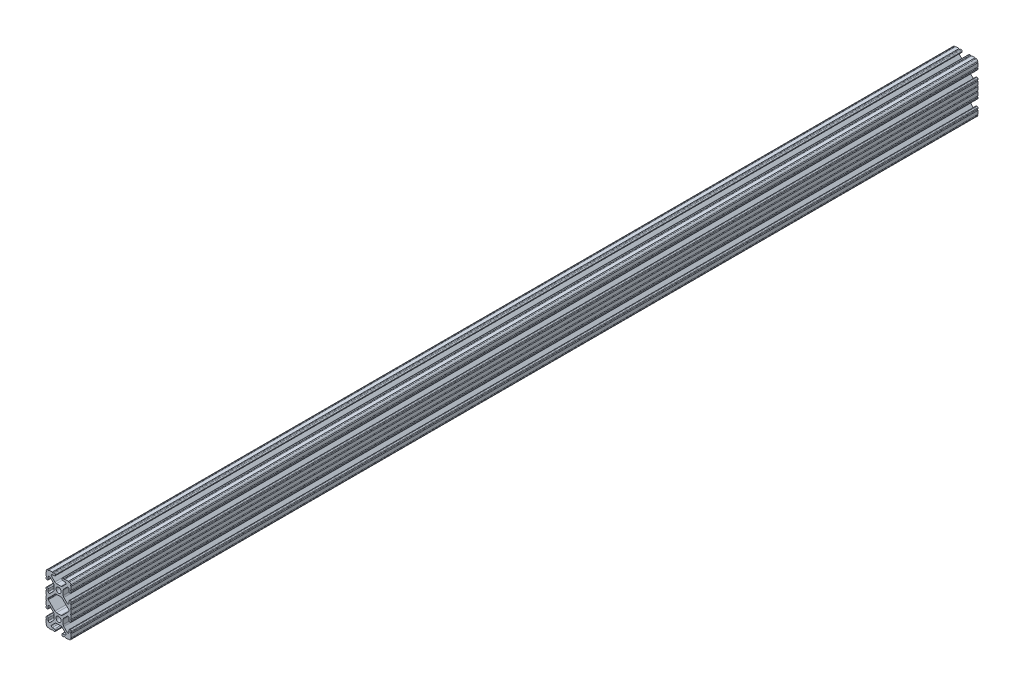
SolidWorks part; units mm, degrees
ref_plane "Front Plane" through (0, 0, 0) normal (0, 0, 1) x (1, 0, 0)
ref_plane "Top Plane" through (0, 0, 0) normal (0, 1, 0) x (1, 0, 0)
ref_plane "Right Plane" through (0, 0, 0) normal (1, 0, 0) x (0, 0, -1)
sketch "Sketch2" plane through (0, 0, 0) normal (0, 0, 1) x (1, 0, 0)
  line L0 (0, 25.4) -> (0, -25.4) construction
  line L1 (-12.7, 0) -> (12.7, 0) construction
  line L2 (3.2512, -25.4) -> (12.7, -25.4)
  line L3 (12.7, -25.4) -> (12.7, -15.9512)
  line L4 (3.2512, -25.4) -> (3.2512, -23.1902)
  line L5 (3.2512, -23.1902) -> (8.9276, -23.1902)
  line L6 (8.9276, -23.1902) -> (3.0856, -17.3482)
  line L7 (0, -12.7) -> (12.7, -25.4) construction
  line L8 (12.7, -15.9512) -> (10.4902, -15.9512)
  line L9 (10.4902, -15.9512) -> (10.4902, -21.6276)
  line L10 (10.4902, -21.6276) -> (4.6482, -15.7856)
  line L11 (3.2512, -25.4) -> (0, -25.4) construction
  line L12 (0, -25.4) -> (-3.2512, -25.4) construction
  line L13 (-3.2512, -25.4) -> (-12.7, -25.4) construction
  line L14 (12.7, 25.4) -> (-12.7, 25.4) construction
  line L15 (0, 12.7) -> (0, -12.7) construction
  circle A0 centre (0, -12.7) radius 2.6035
  arc A1 (6.3485, -23.1902) -> (7.1039, -21.3665) centre (6.3485, -22.1219) ccw construction
  point P8 (0, -17.3482)
  point P16 (-2.6035, -12.7)
  point P18 (2.6035, -12.7)
  point P19 (0, -10.0965)
  point P20 (0, -15.3035)
  point P27 (-12.7, -25.4)
  point P30 (0, 25.4)
  point P31 (12.7, 25.4)
  point P32 (-12.7, 25.4)
  point P33 (12.7, -25.4)
  point P34 (0, -12.7)
  point P35 (0, 12.7)
  point P37 (0, 0)
  point P38 (-3.2512, -25.4)
  point P39 (3.2512, -25.4)
  dimension "Center Hole Diameter" = 5.207
  dimension "Rail Height" = 50.8
  dimension "Rail Width" = 25.4
  dimension "T-Slot Width" = 6.5024
  dimension "Slot Inner Width" = 14.8336
  dimension "Thickness" = 2.2098
  dimension "Slot Depth" = 5.842
  dimension "D1" = 2.2098
  dimension "C to C" = 25.4
sketch "Sketch3" plane through (0, 0, 0) normal (1, 0, 0) x (0, 0, -1)
  line L0 (-457.2, -25.4) -> (457.2, -25.4) construction
  line L1 (-406.4, 0) -> (406.4, 0) construction
  point P6 (-457.2, -25.4)
  point P8 (-406.4, 0)
  point P9 (406.4, 0)
  point P10 (457.2, -25.4)
  dimension "Length" = 914.4
  dimension "D1" = 50.8
sketch "Sketch4" plane through (0, 0, 0) normal (0, 0, 1) x (1, 0, 0)
  line L0 (4.1904, -25.4) -> (10.1173, -25.4)
  line L1 (3.2512, -25.4) -> (12.7, -25.4) construction
  line L2 (3.2512, -25.4) -> (3.2512, -23.1902) construction
  line L3 (3.2512, -23.1902) -> (8.9276, -23.1902) construction
  line L4 (3.2512, -24.1294) -> (3.2512, -24.4608)
  line L5 (4.1904, -23.1902) -> (6.3485, -23.1902)
  line L6 (0, -17.3482) -> (2.164, -17.3482)
  line L7 (8.9276, -23.1902) -> (3.0856, -17.3482) construction
  line L8 (3.7373, -17.9999) -> (7.1039, -21.3665)
  line L9 (12.7, -25.4) -> (12.7, -15.9512) construction
  line L10 (10.4902, -21.6276) -> (4.6482, -15.7856) construction
  line L11 (10.4902, -15.9512) -> (10.4902, -21.6276) construction
  line L12 (10.4902, -19.0485) -> (10.4902, -16.8904)
  line L13 (12.7, -15.9512) -> (10.4902, -15.9512) construction
  line L14 (11.4294, -15.9512) -> (11.7608, -15.9512)
  line L15 (12.7, -16.8904) -> (12.7, -22.8173)
  line L16 (8.6665, -19.8039) -> (5.2999, -16.4373)
  line L17 (4.6482, -12.7) -> (4.6482, -14.864)
  line L19 (0, -17.3482) -> (0, -15.3035)
  line L20 (0, 25.4) -> (0, -25.4) construction
  line L21 (4.6482, -12.7) -> (2.6035, -12.7)
  arc A0 (3.2512, -24.4608) -> (4.1904, -25.4) centre (4.1904, -24.4608) ccw
  circle A1 centre (0, -12.7) radius 2.6035 construction
  arc A2 (3.2512, -24.1294) -> (4.1904, -23.1902) centre (4.1904, -24.1294) cw
  arc A3 (6.3485, -23.1902) -> (7.1039, -21.3665) centre (6.3485, -22.1219) ccw
  arc A4 (2.164, -17.3482) -> (3.7373, -17.9999) centre (2.164, -19.5732) cw
  arc A5 (10.1173, -25.4) -> (12.7, -22.8173) centre (10.1173, -22.8173) ccw
  arc A6 (8.6665, -19.8039) -> (10.4902, -19.0485) centre (9.4219, -19.0485) ccw
  arc A7 (10.4902, -16.8904) -> (11.4294, -15.9512) centre (11.4294, -16.8904) cw
  arc A8 (11.7608, -15.9512) -> (12.7, -16.8904) centre (11.7608, -16.8904) cw
  arc A9 (5.2999, -16.4373) -> (4.6482, -14.864) centre (6.8732, -14.864) cw
  arc A11 (0, -15.3035) -> (2.6035, -12.7) centre (0, -12.7) ccw
  dimension "D1" = 2.5827
  dimension "D2" = 2.225
  dimension "D3" = 0.9392
extrude "Boss-Extrude1" add sketch "Sketch4" along normal mid plane 914.4
sketch "Sketch5" plane through (0, 0, 0) normal (0, 0, 1) x (1, 0, 0)
  line L0 (3.2512, -25.4) -> (12.7, -25.4) construction
  line L1 (4.1904, -23.1902) -> (6.3485, -23.1902) construction
  line L3 (0, -12.7) -> (12.7, -25.4) construction
  line L4 (6.3485, -23.1902) -> (6.3485, -25.4) construction
  line L5 (8.9276, -23.1902) -> (3.0856, -17.3482) construction
  circle A0 centre (10.3562, -25.4) radius 0.5524
  circle A1 centre (5.796, -25.4) radius 0.5524
  circle A2 centre (12.7, -23.0562) radius 0.5524
  circle A3 centre (12.7, -18.496) radius 0.5524
  point P10 (5.2694, -23.1902)
  point P12 (9.4219, -19.0485)
  dimension "D1" = 1.1049
extrude "Cut-Extrude1" cut sketch "Sketch5" against normal through all both and the other way through all
mirror "Mirror1" about plane through (4.6482, -12.7, 457.2) normal (0, -1, 0) of bodies 137 134
sketch "Sketch6" plane through (0, 0, 0) normal (0, 0, 1) x (1, 0, 0)
  line L0 (12.7, -1.7914) -> (12.7, 0)
  line L1 (12.7, 0) -> (9.8037, 0)
  line L2 (-12.7, 0) -> (12.7, 0) construction
  line L3 (9.8037, 0) -> (9.8037, -2.3438)
  line L4 (9.8037, -2.3438) -> (12.1476, -2.3438)
  circle A0 centre (12.7, -2.3438) radius 0.5524 construction
  arc A1 (12.7, -1.7914) -> (12.1476, -2.3438) centre (12.7, -2.3438) ccw
  arc A4 (12.58, -1.8046) -> (12.7, -2.8963) centre (12.7, -2.3438) ccw construction
  arc A6 (9.8037, 0) -> (10.8954, -0.12) centre (10.3562, 0) ccw construction
extrude "Boss-Extrude2" add sketch "Sketch6" along normal mid plane 914.4
sketch "Sketch7" plane through (0, 0, 0) normal (0, 0, 1) x (1, 0, 0)
  line L0 (5.4206, -5.7168) -> (10.3284, -0.809)
  line L1 (3.7373, -7.4001) -> (7.1039, -4.0335) construction
  line L2 (10.4902, -0.4184) -> (10.4902, 0)
  line L3 (0, 0) -> (10.4902, 0)
  line L4 (-12.7, 0) -> (12.7, 0) construction
  line L5 (0, 0) -> (5.4206, -5.7168)
  arc A0 (10.3284, -0.809) -> (10.4902, -0.4184) centre (9.9377, -0.4184) ccw
  arc A3 (12.7, -1.7914) -> (12.7, -2.8963) centre (12.7, -2.3438) ccw construction
extrude "Cut-Extrude2" cut sketch "Sketch7" against normal through all both and the other way through all
mirror "Mirror2" about plane through (0, 0, 0) normal (0, 1, 0) of bodies 139 135
mirror "Mirror3" about plane through (0, 0, 0) normal (1, 0, 0) of bodies 136
equation "\"D1@Boss-Extrude1\"=\"Length@Sketch3\""
equation "\"D1@Sketch2\"=\"Thickness@Sketch2\""
equation "\"D2@Sketch4\"=\"Slot Inner Width@Sketch2\"*0.15"
equation "\"D1@Sketch4\"=\"D3@Sketch4\"*2.75"
equation "\"D3@Sketch4\"=\"Thickness@Sketch2\"*0.425"
equation "\"D1@Sketch5\"=\"Thickness@Sketch2\"*0.5"
equation "\"D1@Boss-Extrude2\"=\"Length@Sketch3\""
